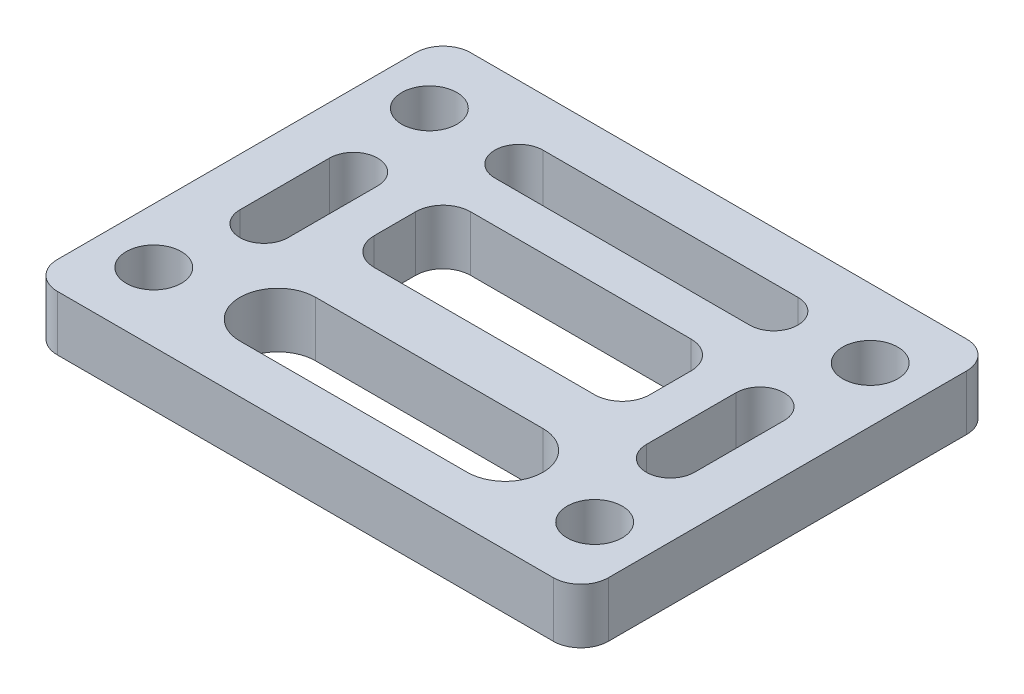
SolidWorks part; units mm, degrees
material "Thornel Mat VMA"
ref_plane "前视基准面" through (0, 0, 0) normal (0, 0, 1) x (1, 0, 0)
ref_plane "上视基准面" through (0, 0, 0) normal (0, 1, 0) x (1, 0, 0)
ref_plane "右视基准面" through (0, 0, 0) normal (1, 0, 0) x (0, 0, -1)
sketch "草图1" plane through (0, 0, 0) normal (0, 1, 0) x (1, 0, 0)
  line L1 (-16, -10) -> (16, -10) construction
  line L2 (-16, -10) -> (-16, 10) construction
  line L3 (-16, 10) -> (16, 10) construction
  line L4 (16, -10) -> (16, 10) construction
  line L5 (-10, 5) -> (10, 5)
  line L6 (-10, 5) -> (-10, -2)
  line L7 (20, -15) -> (-20, -15)
  line L8 (20, -15) -> (20, 15)
  line L9 (20, 15) -> (-20, 15)
  line L10 (-20, -15) -> (-20, 15)
  line L11 (0, 15) -> (0, -15) construction
  line L12 (20, 0) -> (-20, 0) construction
  line L13 (-10, -2) -> (10, -2)
  line L14 (10, 5) -> (10, -2)
  circle A0 centre (-16, 10) radius 2
  circle A1 centre (-16, -10) radius 2
  circle A2 centre (16, 10) radius 2
  circle A3 centre (16, -10) radius 2
  point P0 (0, 10)
  point P4 (-16, 0)
  point P20 (9.7618, -2.1653)
  point P21 (0, 5)
  dimension "D5" = 4
  dimension "D6" = 20
  dimension "D1" = 20
  dimension "D2" = 32
  dimension "D3" = 4
  dimension "D4" = 5
  dimension "D7" = 2
  dimension "D8" = 7
extrude "凸台-拉伸1" add sketch "草图1" along normal blind 4
sketch "草图2" plane through (0, 4, 0) normal (0, 1, 0) x (1, 0, 0)
  line L0 (-9.25, 9.75) -> (9.25, 9.75) construction
  line L1 (-9.25, 11.5) -> (9.25, 11.5)
  line L2 (-9.25, 8) -> (9.25, 8)
  line L3 (-14.75, 3.25) -> (-14.75, -3.25) construction
  line L4 (-13, 3.25) -> (-13, -3.25)
  line L5 (-16.5, 3.25) -> (-16.5, -3.25)
  line L6 (20, 15) -> (-20, 15) construction
  line L7 (-20, -15) -> (20, -15) construction
  line L8 (-10, 5) -> (-10, -2) construction
  line L9 (-20, 15) -> (-20, -15) construction
  line L10 (10, 5) -> (-10, 5) construction
  line L11 (20, -15) -> (20, 15) construction
  line L12 (0, -2.2) -> (0, 2.2) construction
  line L13 (14.75, 3.25) -> (14.75, -3.25) construction
  line L14 (13, 3.25) -> (13, -3.25)
  line L15 (16.5, 3.25) -> (16.5, -3.25)
  line L17 (-8.25, -8.75) -> (8.25, -8.75) construction
  line L18 (-8.25, -11.5) -> (8.25, -11.5)
  line L19 (-8.25, -6) -> (8.25, -6)
  line L20 (0, 9.75) -> (0, -8.75) construction
  line L21 (-10, -2) -> (10, -2) construction
  arc A0 (-9.25, 11.5) -> (-9.25, 8) centre (-9.25, 9.75) ccw
  arc A1 (9.25, 8) -> (9.25, 11.5) centre (9.25, 9.75) ccw
  arc A2 (-13, 3.25) -> (-16.5, 3.25) centre (-14.75, 3.25) ccw
  arc A3 (-16.5, -3.25) -> (-13, -3.25) centre (-14.75, -3.25) ccw
  arc A4 (13, 3.25) -> (16.5, 3.25) centre (14.75, 3.25) cw
  arc A5 (16.5, -3.25) -> (13, -3.25) centre (14.75, -3.25) cw
  arc A6 (-8.25, -11.5) -> (-8.25, -6) centre (-8.25, -8.75) cw
  arc A7 (8.25, -6) -> (8.25, -11.5) centre (8.25, -8.75) cw
  point P2 (0, 9.75)
  point P7 (-14.75, 0)
  point P14 (-14.75, 5)
  point P17 (-14.75, -5)
  point P26 (-11, 9.75)
  point P27 (11, 9.75)
  point P34 (14.75, 0)
  point P43 (0, -8.75)
  point P50 (-11, -8.75)
  dimension "D1" = 10
  dimension "D2" = 10
  dimension "D3" = 3
  dimension "D4" = 3.5
  dimension "D5" = 3
  dimension "D6" = 3.5
  dimension "D7" = 9
  dimension "D8" = 9
  dimension "D9" = 3.5
  dimension "D10" = 4
  dimension "D11" = 9
extrude "切除-拉伸1" cut sketch "草图2" against normal through all
fillet "圆角1" radius 2 8 edges at (10, 2, 2) (10, 2, -5) (-10, 2, -5) (-10, 2, 2) (20, 2, -15) (20, 2, 15) (-20, 2, 15) (-20, 2, -15)
